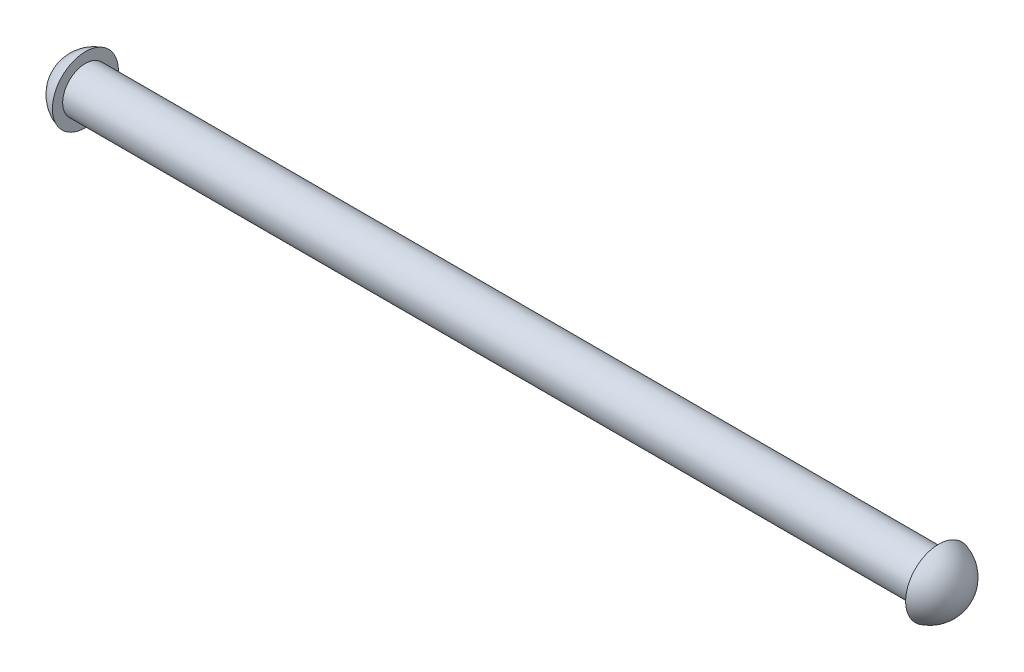
SolidWorks part; units mm, degrees
material "Plain Carbon Steel"
ref_plane "Front Plane" through (0, 0, 0) normal (0, 0, 1) x (1, 0, 0)
ref_plane "Top Plane" through (0, 0, 0) normal (0, 1, 0) x (1, 0, 0)
ref_plane "Right Plane" through (0, 0, 0) normal (1, 0, 0) x (0, 0, -1)
sketch "Sketch1" plane through (0, 0, 0) normal (0, 0, 1) x (1, 0, 0)
  line L0 (-24.0162, 0) -> (26.6571, 0) construction
  line L1 (-37.5, 2) -> (-37.5, 2.9)
  line L2 (-37.5, 0) -> (37.5, 0)
  line L4 (-37.5, 2) -> (37.5, 2)
  line L6 (-37.5, 0) -> (-39.7319, 0)
  line L7 (-37.5, 0) -> (-42.3972, 0) construction
  line L8 (0, 0) -> (0, 6.4135) construction
  line L9 (37.5, 0) -> (39.7319, 0)
  line L10 (37.5, 2) -> (37.5, 2.9)
  arc A0 (-37.5, 2.9) -> (-39.7319, 0) centre (-36.7319, 0) ccw
  arc A1 (37.5, 2.9) -> (39.7319, 0) centre (36.7319, 0) cw
  point P3 (0, 2)
  dimension "D3" = 3
  dimension "D1" = 4
  dimension "D2" = 2.2319
  dimension "D4" = 5.8
  dimension "D5" = 37.5
revolve "Revolve1" add sketch "Sketch1" angle 360 about L2
